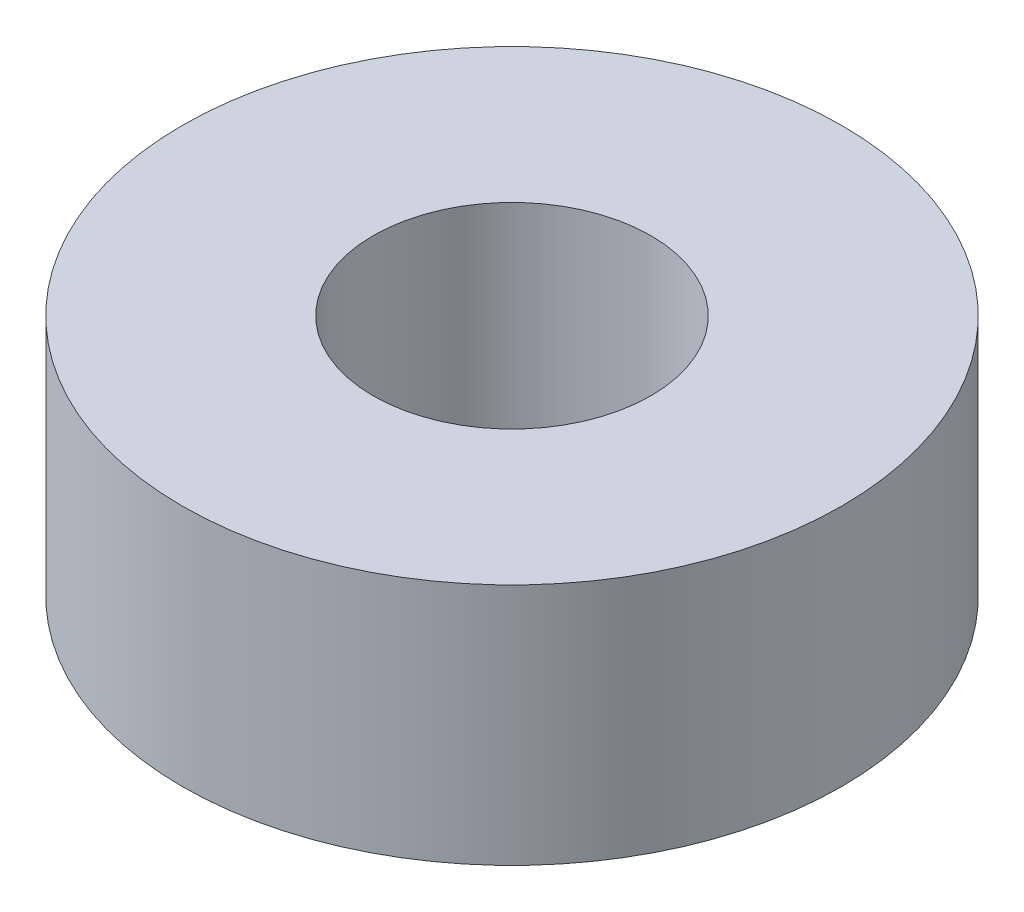
SolidWorks part; units mm, degrees
material "AISI 1020"
ref_plane "Front Plane" through (0, 0, 0) normal (0, 0, 1) x (1, 0, 0)
ref_plane "Top Plane" through (0, 0, 0) normal (0, 1, 0) x (1, 0, 0)
ref_plane "Right Plane" through (0, 0, 0) normal (1, 0, 0) x (0, 0, -1)
sketch "Sketch1" plane through (0, 0, 0) normal (0, 1, 0) x (1, 0, 0)
  circle A0 centre (0, 0) radius 9.5
  circle A1 centre (0, 0) radius 4
  dimension "D1" = 19
  dimension "D2" = 8
extrude "Boss-Extrude1" add sketch "Sketch1" along normal blind 7
